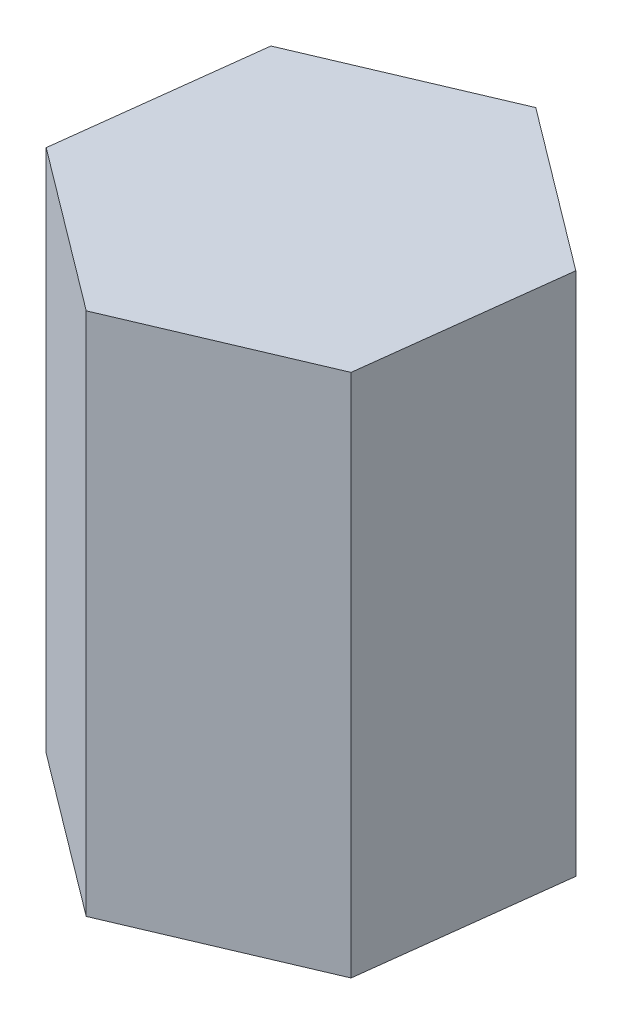
SolidWorks part; units mm, degrees
ref_plane "Front Plane" through (0, 0, 0) normal (0, 0, 1) x (1, 0, 0)
ref_plane "Top Plane" through (0, 0, 0) normal (0, 1, 0) x (1, 0, 0)
ref_plane "Right Plane" through (0, 0, 0) normal (1, 0, 0) x (0, 0, -1)
sketch "Sketch1" plane through (0, 0, 0) normal (0, 1, 0) x (1, 0, 0)
  line L5 (2.3075, -1.7346) -> (2.6559, 1.131)
  line L6 (2.6559, 1.131) -> (0.3485, 2.8656)
  line L7 (0.3485, 2.8656) -> (-2.3075, 1.7346)
  line L8 (-2.3075, 1.7346) -> (-2.6559, -1.131)
  line L9 (-2.6559, -1.131) -> (-0.3485, -2.8656)
  line L10 (-0.3485, -2.8656) -> (2.3075, -1.7346)
  circle A0 centre (0, 0) radius 2.5 construction
extrude "Boss-Extrude1" add sketch "Sketch1" along normal blind 7.5
